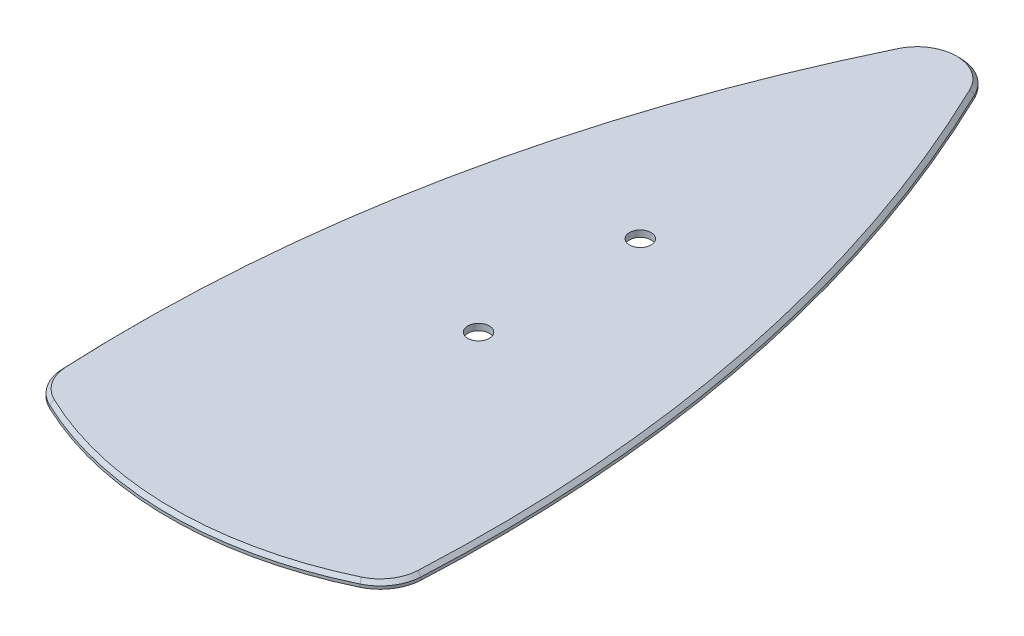
SolidWorks part; units mm, degrees
ref_plane "Front Plane" through (0, 0, 0) normal (0, 0, 1) x (1, 0, 0)
ref_plane "Top Plane" through (0, 0, 0) normal (0, 1, 0) x (1, 0, 0)
ref_plane "Right Plane" through (0, 0, 0) normal (1, 0, 0) x (0, 0, -1)
sketch "Sketch1" plane through (0, 0, 0) normal (0, 1, 0) x (1, 0, 0)
  line L0 (0, 550) -> (0, -550) construction
  arc A0 (-54.0521, 516.0455) -> (54.0521, 516.0455) centre (0, 490) cw
  arc A1 (-54.0521, 516.0455) -> (-249.9284, -449.7924) centre (1747.686, -352.1364) ccw
  arc A2 (-249.9284, -449.7924) -> (-215.9091, -500.9803) centre (-190, -446.8627) ccw
  arc A3 (-215.9091, -500.9803) -> (215.9091, -500.9803) centre (0, -50) ccw
  arc A4 (249.9284, -449.7924) -> (215.9091, -500.9803) centre (190, -446.8627) cw
  arc A5 (54.0521, 516.0455) -> (249.9284, -449.7924) centre (-1747.686, -352.1364) cw
  dimension "D1" = 500
  dimension "D2" = 500
  dimension "D4" = 2000
  dimension "D5" = 60
  dimension "D3" = 1100
extrude "Boss-Extrude1" add sketch "Sketch1" against normal blind 9
sketch "Sketch3" plane through (0, -9, 0) normal (0, -1, 0) x (1, 0, 0)
  line L0 (-180, 551) -> (-255, 476)
  line L1 (-255, 476) -> (-255, -56.4541)
  line L2 (-255, -56.4541) -> (-75, -551)
  line L3 (-75, -551) -> (75, -551)
  line L4 (0, -551) -> (0, 551) construction
  line L5 (180, 551) -> (-180, 551)
  line L6 (255, -56.4541) -> (75, -551)
  line L7 (255, 476) -> (255, -56.4541)
  line L8 (180, 551) -> (255, 476)
  arc A6 (-249.9284, 449.7924) -> (-54.0521, -516.0455) centre (1747.686, 352.1364) ccw
  arc A7 (-54.0521, -516.0455) -> (54.0521, -516.0455) centre (0, -490) ccw
  arc A8 (54.0521, -516.0455) -> (249.9284, 449.7924) centre (-1747.686, 352.1364) ccw
  arc A9 (249.9284, 449.7924) -> (215.9091, 500.9803) centre (190, 446.8627) ccw
  arc A10 (215.9091, 500.9803) -> (-215.9091, 500.9803) centre (0, 50) ccw
  arc A11 (-215.9091, 500.9803) -> (-249.9284, 449.7924) centre (-190, 446.8627) ccw
  arc A12 (-249.9284, 449.7924) -> (-54.0521, -516.0455) centre (1747.686, 352.1364) ccw
  arc A13 (-54.0521, -516.0455) -> (54.0521, -516.0455) centre (0, -490) ccw
  arc A14 (54.0521, -516.0455) -> (249.9284, 449.7924) centre (-1747.686, 352.1364) ccw
  arc A15 (249.9284, 449.7924) -> (215.9091, 500.9803) centre (190, 446.8627) ccw
  arc A16 (215.9091, 500.9803) -> (-215.9091, 500.9803) centre (0, 50) ccw
  arc A17 (-215.9091, 500.9803) -> (-249.9284, 449.7924) centre (-190, 446.8627) ccw
  dimension "D2" = 551
  dimension "D3" = 255
  dimension "D4" = 45
  dimension "D5" = 75
  dimension "D6" = 20
  dimension "D7" = 551
  dimension "D8" = 150
  dimension "D1" = 0
extrude "Boss-Extrude2" [suppressed] add sketch "Sketch3" against normal up to surface (18 mm away)
chamfer "Chamfer1" distance 5 angle 45 6 edges at (0, 0, -550) (-212.4111, 0, -45.3802) (212.4111, 0, -45.3802) (-239.9707, 0, 480.0731) (239.9707, 0, 480.0731) (0, 0, 550)
sketch "Sketch2" plane through (0, 0, 0) normal (0, 1, 0) x (1, 0, 0)
  line L0 (0, -120) -> (0, 105) construction
  circle A0 centre (0, 105) radius 15
  circle A1 centre (0, -120) radius 15
  dimension "D2" = 30
  dimension "D1" = 225
  dimension "D3" = 120
extrude "Cut-Extrude1" cut sketch "Sketch2" against normal through all
